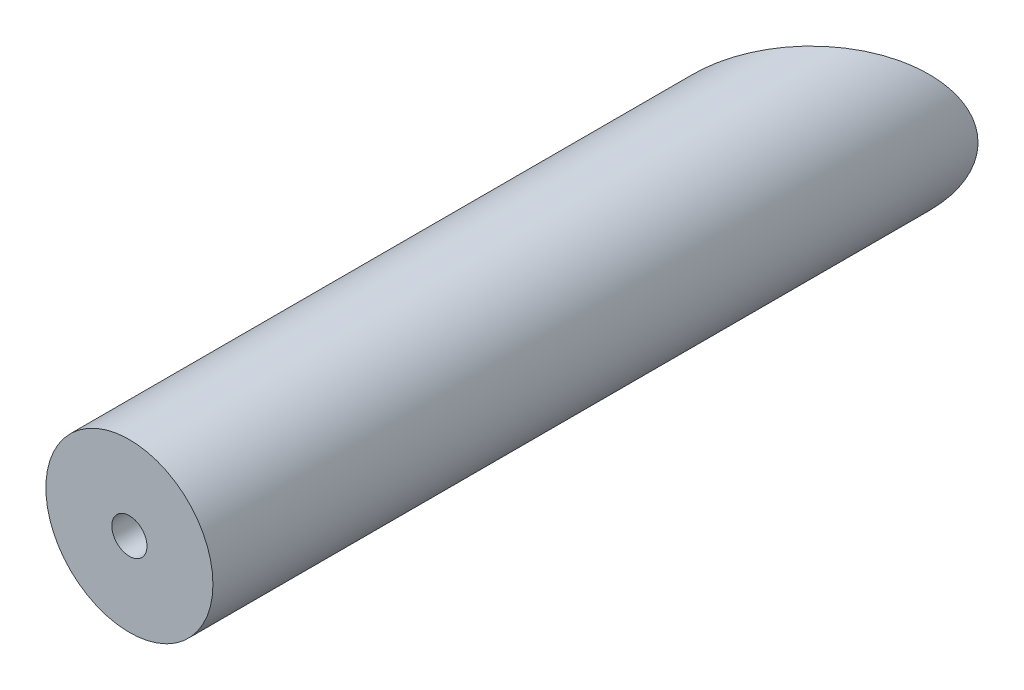
SolidWorks part; units mm, degrees
ref_plane "Front Plane" through (0, 0, 0) normal (0, 0, 1) x (1, 0, 0)
ref_plane "Top Plane" through (0, 0, 0) normal (0, 1, 0) x (1, 0, 0)
ref_plane "Right Plane" through (0, 0, 0) normal (1, 0, 0) x (0, 0, -1)
sketch "Sketch1" plane through (0, 0, 0) normal (0, 0, 1) x (1, 0, 0)
  circle A0 centre (0, 0) radius 30.1625
  circle A1 centre (0, 0) radius 6.35
extrude "Boss-Extrude1" add sketch "Sketch1" along normal blind 276.225
sketch "Sketch2" plane through (0, 0, 0) normal (0, 1, 0) x (1, 0, 0)
  line L0 (30.1625, 0) -> (-40.1403, -70.3028)
  line L1 (-40.1403, -70.3028) -> (-40.1403, 5.4647)
  line L2 (-40.1403, 5.4647) -> (30.1625, 5.4647)
  line L3 (30.1625, 5.4647) -> (30.1625, 0)
extrude "Cut-Extrude1" cut sketch "Sketch2" against normal through all both and the other way through all
